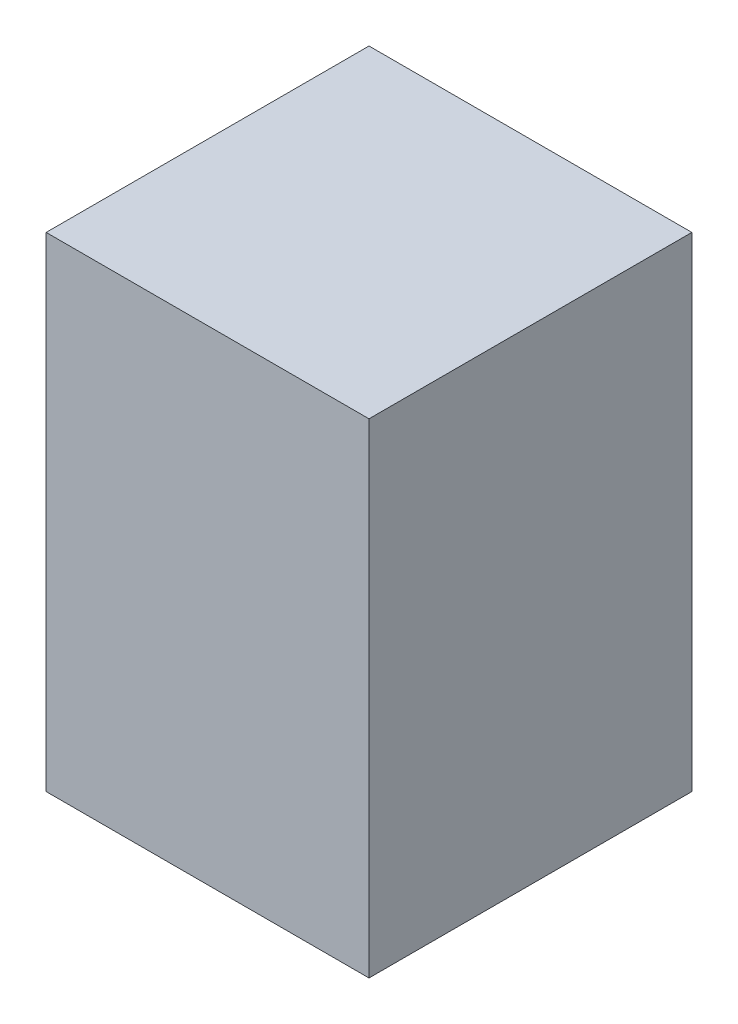
SolidWorks part; units mm, degrees
ref_plane "Front Plane" through (0, 0, 0) normal (0, 0, 1) x (1, 0, 0)
ref_plane "Top Plane" through (0, 0, 0) normal (0, 1, 0) x (1, 0, 0)
ref_plane "Right Plane" through (0, 0, 0) normal (1, 0, 0) x (0, 0, -1)
sketch "Sketch1" plane through (0, 0, 0) normal (0, 1, 0) x (1, 0, 0)
  line L1 (-20, -20) -> (20, -20)
  line L2 (-20, -20) -> (-20, 20)
  line L3 (-20, 20) -> (20, 20)
  line L4 (20, -20) -> (20, 20)
  line L5 (-20, -20) -> (20, 20) construction
  line L6 (-20, 20) -> (20, -20) construction
  point P0 (0, 0)
  dimension "D1" = 40
extrude "Boss-Extrude1" add sketch "Sketch1" along normal blind 60
sketch "Sketch3" plane through (0, 0, 0) normal (1, 0, 0) x (0, 0, -1)
  line L0 (-5, 0) -> (-2.5, -6)
  line L1 (-20, 0) -> (20, 0) construction
  line L2 (-2.5, -6) -> (2.5, -6)
  line L3 (2.5, -6) -> (5, 0)
  line L4 (5, 0) -> (-5, 0)
  line L5 (0, 0) -> (0, -6) construction
  circle A0 centre (0, -3) radius 1
  dimension "D2" = 2
  dimension "D1" = 6
  dimension "D3" = 10
  dimension "D4" = 5
  dimension "D5" = 3
extrude "Boss-Extrude2" add sketch "Sketch3" along normal mid plane 10
sketch "Sketch4" plane through (0, 0, 0) normal (1, 0, 0) x (0, 0, -1)
  line L0 (-9.0918, 0) -> (10.1525, 0)
  line L1 (-20, 0) -> (20, 0) construction
  line L2 (10.1525, 0) -> (10.1525, -7.3972)
  line L3 (10.1525, -7.3972) -> (-9.0918, -7.3972)
  line L4 (-9.0918, -7.3972) -> (-9.0918, 0)
extrude "Cut-Extrude1" cut sketch "Sketch4" against normal mid plane 7.5
